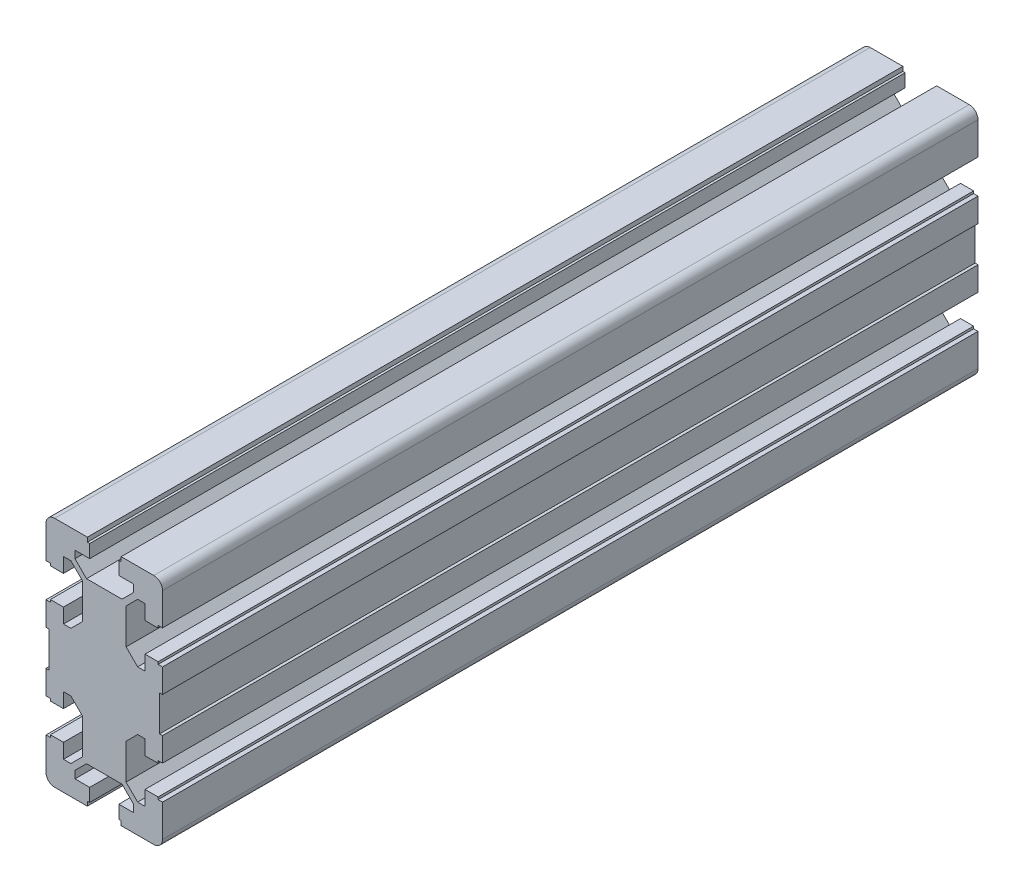
SolidWorks part; units mm, degrees
ref_plane "Front Plane" through (0, 0, 0) normal (0, 0, 1) x (1, 0, 0)
ref_plane "Top Plane" through (0, 0, 0) normal (0, 1, 0) x (1, 0, 0)
ref_plane "Right Plane" through (0, 0, 0) normal (1, 0, 0) x (0, 0, -1)
sketch "Sketch1" plane through (0, 0, 0) normal (0, 0, 1) x (1, 0, 0)
  line L0 (10.6358, -8.0584) -> (17, -8.0584)
  line L1 (19, -6.1084) -> (20, -6.1084)
  line L2 (19, 6.1084) -> (19, -6.1084)
  line L3 (-10.05, -34) -> (-10.05, -31.4642)
  line L4 (-18.5, -34.6084) -> (-18.5, -29.6084)
  line L5 (-20, -25.9084) -> (-20, -37)
  line L6 (17, -8.0584) -> (17, 8.0584)
  line L7 (5.5, -14.6084) -> (2.3979, -14.6084)
  line L8 (-17, -40) -> (-5.8, -40)
  line L9 (-5, -34) -> (-10.05, -34)
  line L10 (-11.75, -34.6084) -> (-11.75, -35.6084)
  line L11 (-11.75, -35.6084) -> (-9.5, -35.6084)
  line L12 (-9.5, -38.6084) -> (-14.5, -38.6084)
  line L13 (-14.5, -38.6084) -> (-14.5, -37.3584)
  line L14 (-17.25, -34.6084) -> (-18.5, -34.6084)
  line L15 (4.5833, -18.1101) -> (5.5, -17.7105)
  line L16 (-5.8, -40) -> (-5.8, -38.5)
  line L17 (-5.8, -38.5) -> (-5, -38.5)
  line L18 (-5, -38.5) -> (-5, -34)
  line L19 (2.3979, -14.6084) -> (1.9983, -15.5251)
  line L20 (5.5, -17.7105) -> (5.5, -14.6084)
  line L21 (18.5, -15.1084) -> (14, -15.1084)
  line L22 (18.5, -14.3084) -> (18.5, -15.1084)
  line L23 (14, -10.0584) -> (11.4642, -10.0584)
  line L24 (14, -15.1084) -> (14, -10.0584)
  line L25 (20, -14.3084) -> (18.5, -14.3084)
  line L26 (0, 44.6651) -> (0, -44.6651) construction
  line L27 (11.4642, -10.0584) -> (7.5, -14.0226)
  line L28 (5.5, -25.6084) -> (5.5, -22.5063)
  line L29 (2.3979, -25.6084) -> (5.5, -25.6084)
  line L30 (1.9983, -24.6917) -> (2.3979, -25.6084)
  line L31 (5.5, -22.5063) -> (4.5833, -22.1067)
  line L32 (14, -25.1084) -> (18.5, -25.1084)
  line L33 (18.5, -25.1084) -> (18.5, -25.9084)
  line L34 (18.5, -25.9084) -> (20, -25.9084)
  line L35 (11.4642, -30.1584) -> (14, -30.1584)
  line L36 (15.5, -31.8584) -> (14.5, -31.8584)
  line L37 (15.5, -29.6084) -> (15.5, -31.8584)
  line L38 (14, -30.1584) -> (14, -25.1084)
  line L39 (-20, -6.1084) -> (-20, -14.3084)
  line L40 (-6.0858, -12.6084) -> (-10.6358, -8.0584)
  line L41 (-7.5, -14.0226) -> (-7.5, -26.1942)
  line L42 (10.05, -31.4642) -> (6.0858, -27.5)
  line L43 (-7.5, -26.1942) -> (-11.4642, -30.1584)
  line L44 (-10.05, -31.4642) -> (-6.0858, -27.5)
  line L45 (-14, -30.1584) -> (-14, -25.1084)
  line L46 (-15.5, -29.6084) -> (-15.5, -31.8584)
  line L47 (-15.5, -31.8584) -> (-14.5, -31.8584)
  line L48 (-11.4642, -30.1584) -> (-14, -30.1584)
  line L49 (-18.5, -25.9084) -> (-20, -25.9084)
  line L50 (-18.5, -25.1084) -> (-18.5, -25.9084)
  line L51 (-14, -25.1084) -> (-18.5, -25.1084)
  line L52 (7.5, -26.1942) -> (11.4642, -30.1584)
  line L53 (-6.0858, -27.5) -> (6.0858, -27.5)
  line L54 (7.5, -14.0226) -> (7.5, -26.1942)
  line L55 (-5.5, -22.5063) -> (-4.5833, -22.1067)
  line L56 (-1.9983, -24.6917) -> (-2.3979, -25.6084)
  line L57 (-2.3979, -25.6084) -> (-5.5, -25.6084)
  line L58 (-5.5, -25.6084) -> (-5.5, -22.5063)
  line L59 (6.0858, -12.6084) -> (10.6358, -8.0584)
  line L60 (20, -6.1084) -> (20, -14.3084)
  line L61 (5, -38.5) -> (5, -34)
  line L62 (5.8, -38.5) -> (5, -38.5)
  line L63 (-11.4642, -10.0584) -> (-7.5, -14.0226)
  line L64 (-20, -14.3084) -> (-18.5, -14.3084)
  line L65 (-14, -15.1084) -> (-14, -10.0584)
  line L66 (-14, -10.0584) -> (-11.4642, -10.0584)
  line L67 (-18.5, -14.3084) -> (-18.5, -15.1084)
  line L68 (-18.5, -15.1084) -> (-14, -15.1084)
  line L69 (5.8, -40) -> (5.8, -38.5)
  line L70 (-5.5, -17.7105) -> (-5.5, -14.6084)
  line L71 (-2.3979, -14.6084) -> (-1.9983, -15.5251)
  line L72 (17.25, -34.6084) -> (18.5, -34.6084)
  line L73 (-4.5833, -18.1101) -> (-5.5, -17.7105)
  line L74 (14.5, -38.6084) -> (14.5, -37.3584)
  line L75 (6.0858, -12.6084) -> (-6.0858, -12.6084)
  line L76 (-5.5, -14.6084) -> (-2.3979, -14.6084)
  line L77 (9.5, -38.6084) -> (14.5, -38.6084)
  line L78 (11.75, -35.6084) -> (9.5, -35.6084)
  line L79 (-17, -8.0584) -> (-17, 8.0584)
  line L80 (-19, 6.1084) -> (-19, -6.1084)
  line L81 (-19, -6.1084) -> (-20, -6.1084)
  line L82 (-10.6358, -8.0584) -> (-17, -8.0584)
  line L83 (11.75, -34.6084) -> (11.75, -35.6084)
  line L84 (5, -34) -> (10.05, -34)
  line L85 (17, -40) -> (5.8, -40)
  line L86 (20, -25.9084) -> (20, -37)
  line L87 (18.5, -34.6084) -> (18.5, -29.6084)
  line L88 (10.05, -34) -> (10.05, -31.4642)
  line L89 (10.05, 34) -> (10.05, 31.4642)
  line L90 (18.5, 34.6084) -> (18.5, 29.6084)
  line L91 (20, 25.9084) -> (20, 37)
  line L92 (17, 40) -> (5.8, 40)
  line L93 (5, 34) -> (10.05, 34)
  line L94 (11.75, 34.6084) -> (11.75, 35.6084)
  line L95 (-10.6358, 8.0584) -> (-17, 8.0584)
  line L96 (-19, 6.1084) -> (-20, 6.1084)
  line L97 (11.75, 35.6084) -> (9.5, 35.6084)
  line L98 (9.5, 38.6084) -> (14.5, 38.6084)
  line L99 (-5.5, 14.6084) -> (-2.3979, 14.6084)
  line L100 (6.0858, 12.6084) -> (-6.0858, 12.6084)
  line L101 (14.5, 38.6084) -> (14.5, 37.3584)
  line L102 (-4.5833, 18.1101) -> (-5.5, 17.7105)
  line L103 (17.25, 34.6084) -> (18.5, 34.6084)
  line L104 (-2.3979, 14.6084) -> (-1.9983, 15.5251)
  line L105 (-5.5, 17.7105) -> (-5.5, 14.6084)
  line L106 (5.8, 40) -> (5.8, 38.5)
  line L107 (-18.5, 15.1084) -> (-14, 15.1084)
  line L108 (-18.5, 14.3084) -> (-18.5, 15.1084)
  line L109 (-14, 10.0584) -> (-11.4642, 10.0584)
  line L110 (-14, 15.1084) -> (-14, 10.0584)
  line L111 (-20, 14.3084) -> (-18.5, 14.3084)
  line L112 (-11.4642, 10.0584) -> (-7.5, 14.0226)
  line L113 (5.8, 38.5) -> (5, 38.5)
  line L114 (5, 38.5) -> (5, 34)
  line L115 (20, 6.1084) -> (20, 14.3084)
  line L116 (6.0858, 12.6084) -> (10.6358, 8.0584)
  line L117 (-5.5, 25.6084) -> (-5.5, 22.5063)
  line L118 (-2.3979, 25.6084) -> (-5.5, 25.6084)
  line L119 (-1.9983, 24.6917) -> (-2.3979, 25.6084)
  line L120 (-5.5, 22.5063) -> (-4.5833, 22.1067)
  line L121 (7.5, 14.0226) -> (7.5, 26.1942)
  line L122 (-6.0858, 27.5) -> (6.0858, 27.5)
  line L123 (7.5, 26.1942) -> (11.4642, 30.1584)
  line L124 (-14, 25.1084) -> (-18.5, 25.1084)
  line L125 (-18.5, 25.1084) -> (-18.5, 25.9084)
  line L126 (-18.5, 25.9084) -> (-20, 25.9084)
  line L127 (-11.4642, 30.1584) -> (-14, 30.1584)
  line L128 (-15.5, 31.8584) -> (-14.5, 31.8584)
  line L129 (-15.5, 29.6084) -> (-15.5, 31.8584)
  line L130 (-14, 30.1584) -> (-14, 25.1084)
  line L131 (-10.05, 31.4642) -> (-6.0858, 27.5)
  line L132 (-7.5, 26.1942) -> (-11.4642, 30.1584)
  line L133 (10.05, 31.4642) -> (6.0858, 27.5)
  line L134 (-7.5, 14.0226) -> (-7.5, 26.1942)
  line L135 (-6.0858, 12.6084) -> (-10.6358, 8.0584)
  line L136 (-20, 6.1084) -> (-20, 14.3084)
  line L137 (14, 30.1584) -> (14, 25.1084)
  line L138 (15.5, 29.6084) -> (15.5, 31.8584)
  line L139 (15.5, 31.8584) -> (14.5, 31.8584)
  line L140 (11.4642, 30.1584) -> (14, 30.1584)
  line L141 (18.5, 25.9084) -> (20, 25.9084)
  line L142 (18.5, 25.1084) -> (18.5, 25.9084)
  line L143 (14, 25.1084) -> (18.5, 25.1084)
  line L144 (5.5, 22.5063) -> (4.5833, 22.1067)
  line L145 (1.9983, 24.6917) -> (2.3979, 25.6084)
  line L146 (2.3979, 25.6084) -> (5.5, 25.6084)
  line L147 (5.5, 25.6084) -> (5.5, 22.5063)
  line L148 (11.4642, 10.0584) -> (7.5, 14.0226)
  line L149 (20, 14.3084) -> (18.5, 14.3084)
  line L150 (14, 15.1084) -> (14, 10.0584)
  line L151 (14, 10.0584) -> (11.4642, 10.0584)
  line L152 (18.5, 14.3084) -> (18.5, 15.1084)
  line L153 (18.5, 15.1084) -> (14, 15.1084)
  line L154 (5.5, 17.7105) -> (5.5, 14.6084)
  line L155 (2.3979, 14.6084) -> (1.9983, 15.5251)
  line L156 (-5, 38.5) -> (-5, 34)
  line L157 (-5.8, 38.5) -> (-5, 38.5)
  line L158 (-5.8, 40) -> (-5.8, 38.5)
  line L159 (4.5833, 18.1101) -> (5.5, 17.7105)
  line L160 (-17.25, 34.6084) -> (-18.5, 34.6084)
  line L161 (-14.5, 38.6084) -> (-14.5, 37.3584)
  line L162 (-9.5, 38.6084) -> (-14.5, 38.6084)
  line L163 (-11.75, 35.6084) -> (-9.5, 35.6084)
  line L164 (-11.75, 34.6084) -> (-11.75, 35.6084)
  line L165 (-5, 34) -> (-10.05, 34)
  line L166 (-17, 40) -> (-5.8, 40)
  line L167 (5.5, 14.6084) -> (2.3979, 14.6084)
  line L168 (-20, 25.9084) -> (-20, 37)
  line L169 (-18.5, 34.6084) -> (-18.5, 29.6084)
  line L170 (-10.05, 34) -> (-10.05, 31.4642)
  line L171 (19, 6.1084) -> (20, 6.1084)
  line L172 (10.6358, 8.0584) -> (17, 8.0584)
  line L175 (-39.3803, 0) -> (39.3803, 0) construction
  arc A0 (-11.75, -34.6084) -> (-14.5, -31.8584) centre (-14.5, -34.6084) ccw
  arc A1 (15.5, -29.6084) -> (18.5, -29.6084) centre (17, -29.6084) cw
  arc A2 (-9.5, -38.6084) -> (-9.5, -35.6084) centre (-9.5, -37.1084) ccw
  arc A3 (-20, -37) -> (-17, -40) centre (-17, -37) ccw
  arc A4 (-17.25, -34.6084) -> (-14.5, -37.3584) centre (-14.5, -34.6084) ccw
  arc A5 (4.5833, -18.1101) -> (4.5833, -22.1067) centre (0, -20.1084) cw
  arc A6 (17.25, -34.6084) -> (14.5, -37.3584) centre (14.5, -34.6084) cw
  arc A7 (20, -37) -> (17, -40) centre (17, -37) cw
  arc A8 (9.5, -38.6084) -> (9.5, -35.6084) centre (9.5, -37.1084) cw
  arc A9 (11.75, -34.6084) -> (14.5, -31.8584) centre (14.5, -34.6084) cw
  arc A10 (-4.5833, -18.1101) -> (-4.5833, -22.1067) centre (0, -20.1084) ccw
  arc A11 (-15.5, -29.6084) -> (-18.5, -29.6084) centre (-17, -29.6084) ccw
  arc A12 (-1.9983, -24.6917) -> (1.9983, -24.6917) centre (0, -20.1084) ccw
  arc A13 (1.9983, -15.5251) -> (-1.9983, -15.5251) centre (0, -20.1084) ccw
  arc A14 (1.9983, 15.5251) -> (-1.9983, 15.5251) centre (0, 20.1084) cw
  arc A15 (-1.9983, 24.6917) -> (1.9983, 24.6917) centre (0, 20.1084) cw
  arc A16 (-15.5, 29.6084) -> (-18.5, 29.6084) centre (-17, 29.6084) cw
  arc A17 (-4.5833, 18.1101) -> (-4.5833, 22.1067) centre (0, 20.1084) cw
  arc A18 (11.75, 34.6084) -> (14.5, 31.8584) centre (14.5, 34.6084) ccw
  arc A19 (9.5, 38.6084) -> (9.5, 35.6084) centre (9.5, 37.1084) ccw
  arc A20 (20, 37) -> (17, 40) centre (17, 37) ccw
  arc A21 (17.25, 34.6084) -> (14.5, 37.3584) centre (14.5, 34.6084) ccw
  arc A22 (4.5833, 18.1101) -> (4.5833, 22.1067) centre (0, 20.1084) ccw
  arc A23 (-17.25, 34.6084) -> (-14.5, 37.3584) centre (-14.5, 34.6084) cw
  arc A24 (-20, 37) -> (-17, 40) centre (-17, 37) cw
  arc A25 (-9.5, 38.6084) -> (-9.5, 35.6084) centre (-9.5, 37.1084) cw
  arc A26 (15.5, 29.6084) -> (18.5, 29.6084) centre (17, 29.6084) ccw
  arc A27 (-11.75, 34.6084) -> (-14.5, 31.8584) centre (-14.5, 34.6084) cw
  point P44 (0, -12.6084)
  point P77 (0, -27.5)
  point P143 (0, 27.5)
  point P144 (0, 12.6084)
  point P156 (-19, 0)
  point P157 (-17, 0)
  point P230 (17, 0)
  point P231 (19, 0)
  dimension "D3" = 10
  dimension "D1" = 40
  dimension "D2" = 80
  dimension "D4" = 10
  dimension "D5" = 10
extrude "Extrude1" add sketch "Sketch1" against normal blind 200
sketch "Sketch2" plane through (0, 0, 0) normal (0, 0, 1) x (1, 0, 0)
  line L96 (-17, -40) -> (-5.8, -40)
  line L97 (-5.8, -40) -> (-5.8, -38.5)
  line L98 (-5.8, -38.5) -> (-5, -38.5)
  line L99 (-5, -38.5) -> (-5, -34)
  line L100 (-5, -34) -> (-10.05, -34)
  line L101 (-10.05, -34) -> (-10.05, -31.4642)
  line L102 (-10.05, -31.4642) -> (-6.0858, -27.5)
  line L103 (-6.0858, -27.5) -> (6.0858, -27.5)
  line L104 (6.0858, -27.5) -> (10.05, -31.4642)
  line L105 (10.05, -31.4642) -> (10.05, -34)
  line L106 (10.05, -34) -> (5, -34)
  line L107 (5, -34) -> (5, -38.5)
  line L108 (5, -38.5) -> (5.8, -38.5)
  line L109 (5.8, -38.5) -> (5.8, -40)
  line L110 (5.8, -40) -> (17, -40)
  line L111 (20, -37) -> (20, -25.9084)
  line L112 (20, -25.9084) -> (18.5, -25.9084)
  line L113 (18.5, -25.9084) -> (18.5, -25.1084)
  line L114 (18.5, -25.1084) -> (14, -25.1084)
  line L115 (14, -25.1084) -> (14, -30.1584)
  line L116 (14, -30.1584) -> (11.4642, -30.1584)
  line L117 (11.4642, -30.1584) -> (7.5, -26.1942)
  line L118 (7.5, -26.1942) -> (7.5, -14.0226)
  line L119 (7.5, -14.0226) -> (11.4642, -10.0584)
  line L120 (11.4642, -10.0584) -> (14, -10.0584)
  line L121 (14, -10.0584) -> (14, -15.1084)
  line L122 (14, -15.1084) -> (18.5, -15.1084)
  line L123 (18.5, -15.1084) -> (18.5, -14.3084)
  line L124 (18.5, -14.3084) -> (20, -14.3084)
  line L125 (20, -14.3084) -> (20, -6.1084)
  line L126 (20, -6.1084) -> (19, -6.1084)
  line L127 (19, -6.1084) -> (19, 6.1084)
  line L128 (19, 6.1084) -> (20, 6.1084)
  line L129 (20, 6.1084) -> (20, 14.3084)
  line L130 (20, 14.3084) -> (18.5, 14.3084)
  line L131 (18.5, 14.3084) -> (18.5, 15.1084)
  line L132 (18.5, 15.1084) -> (14, 15.1084)
  line L133 (14, 15.1084) -> (14, 10.0584)
  line L134 (14, 10.0584) -> (11.4642, 10.0584)
  line L135 (11.4642, 10.0584) -> (7.5, 14.0226)
  line L136 (7.5, 14.0226) -> (7.5, 26.1942)
  line L137 (7.5, 26.1942) -> (11.4642, 30.1584)
  line L138 (11.4642, 30.1584) -> (14, 30.1584)
  line L139 (14, 30.1584) -> (14, 25.1084)
  line L140 (14, 25.1084) -> (18.5, 25.1084)
  line L141 (18.5, 25.1084) -> (18.5, 25.9084)
  line L142 (18.5, 25.9084) -> (20, 25.9084)
  line L143 (20, 25.9084) -> (20, 37)
  line L144 (17, 40) -> (5.8, 40)
  line L145 (5.8, 40) -> (5.8, 38.5)
  line L146 (5.8, 38.5) -> (5, 38.5)
  line L147 (5, 38.5) -> (5, 34)
  line L148 (5, 34) -> (10.05, 34)
  line L149 (10.05, 34) -> (10.05, 31.4642)
  line L150 (10.05, 31.4642) -> (6.0858, 27.5)
  line L151 (6.0858, 27.5) -> (-6.0858, 27.5)
  line L152 (-6.0858, 27.5) -> (-10.05, 31.4642)
  line L153 (-10.05, 31.4642) -> (-10.05, 34)
  line L154 (-10.05, 34) -> (-5, 34)
  line L155 (-5, 34) -> (-5, 38.5)
  line L156 (-5, 38.5) -> (-5.8, 38.5)
  line L157 (-5.8, 38.5) -> (-5.8, 40)
  line L158 (-5.8, 40) -> (-17, 40)
  line L159 (-20, 37) -> (-20, 25.9084)
  line L160 (-20, 25.9084) -> (-18.5, 25.9084)
  line L161 (-18.5, 25.9084) -> (-18.5, 25.1084)
  line L162 (-18.5, 25.1084) -> (-14, 25.1084)
  line L163 (-14, 25.1084) -> (-14, 30.1584)
  line L164 (-14, 30.1584) -> (-11.4642, 30.1584)
  line L165 (-11.4642, 30.1584) -> (-7.5, 26.1942)
  line L166 (-7.5, 26.1942) -> (-7.5, 14.0226)
  line L167 (-7.5, 14.0226) -> (-11.4642, 10.0584)
  line L168 (-11.4642, 10.0584) -> (-14, 10.0584)
  line L169 (-14, 10.0584) -> (-14, 15.1084)
  line L170 (-14, 15.1084) -> (-18.5, 15.1084)
  line L171 (-18.5, 15.1084) -> (-18.5, 14.3084)
  line L172 (-18.5, 14.3084) -> (-20, 14.3084)
  line L173 (-20, 14.3084) -> (-20, 6.1084)
  line L174 (-20, 6.1084) -> (-19, 6.1084)
  line L175 (-19, 6.1084) -> (-19, -6.1084)
  line L176 (-19, -6.1084) -> (-20, -6.1084)
  line L177 (-20, -6.1084) -> (-20, -14.3084)
  line L178 (-20, -14.3084) -> (-18.5, -14.3084)
  line L179 (-18.5, -14.3084) -> (-18.5, -15.1084)
  line L180 (-18.5, -15.1084) -> (-14, -15.1084)
  line L181 (-14, -15.1084) -> (-14, -10.0584)
  line L182 (-14, -10.0584) -> (-11.4642, -10.0584)
  line L183 (-11.4642, -10.0584) -> (-7.5, -14.0226)
  line L184 (-7.5, -14.0226) -> (-7.5, -26.1942)
  line L185 (-7.5, -26.1942) -> (-11.4642, -30.1584)
  line L186 (-11.4642, -30.1584) -> (-14, -30.1584)
  line L187 (-14, -30.1584) -> (-14, -25.1084)
  line L188 (-14, -25.1084) -> (-18.5, -25.1084)
  line L189 (-18.5, -25.1084) -> (-18.5, -25.9084)
  line L190 (-18.5, -25.9084) -> (-20, -25.9084)
  line L191 (-20, -25.9084) -> (-20, -37)
  line L192 (-17, -40) -> (-5.8, -40)
  line L193 (-5.8, -40) -> (-5.8, -38.5)
  line L194 (-5.8, -38.5) -> (-5, -38.5)
  line L195 (-5, -38.5) -> (-5, -34)
  line L196 (-5, -34) -> (-10.05, -34)
  line L197 (-10.05, -34) -> (-10.05, -31.4642)
  line L198 (-10.05, -31.4642) -> (-6.0858, -27.5)
  line L199 (-6.0858, -27.5) -> (6.0858, -27.5)
  line L200 (6.0858, -27.5) -> (10.05, -31.4642)
  line L201 (10.05, -31.4642) -> (10.05, -34)
  line L202 (10.05, -34) -> (5, -34)
  line L203 (5, -34) -> (5, -38.5)
  line L204 (5, -38.5) -> (5.8, -38.5)
  line L205 (5.8, -38.5) -> (5.8, -40)
  line L206 (5.8, -40) -> (17, -40)
  line L207 (20, -37) -> (20, -25.9084)
  line L208 (20, -25.9084) -> (18.5, -25.9084)
  line L209 (18.5, -25.9084) -> (18.5, -25.1084)
  line L210 (18.5, -25.1084) -> (14, -25.1084)
  line L211 (14, -25.1084) -> (14, -30.1584)
  line L212 (14, -30.1584) -> (11.4642, -30.1584)
  line L213 (11.4642, -30.1584) -> (7.5, -26.1942)
  line L214 (7.5, -26.1942) -> (7.5, -14.0226)
  line L215 (7.5, -14.0226) -> (11.4642, -10.0584)
  line L216 (11.4642, -10.0584) -> (14, -10.0584)
  line L217 (14, -10.0584) -> (14, -15.1084)
  line L218 (14, -15.1084) -> (18.5, -15.1084)
  line L219 (18.5, -15.1084) -> (18.5, -14.3084)
  line L220 (18.5, -14.3084) -> (20, -14.3084)
  line L221 (20, -14.3084) -> (20, -6.1084)
  line L222 (20, -6.1084) -> (19, -6.1084)
  line L223 (19, -6.1084) -> (19, 6.1084)
  line L224 (19, 6.1084) -> (20, 6.1084)
  line L225 (20, 6.1084) -> (20, 14.3084)
  line L226 (20, 14.3084) -> (18.5, 14.3084)
  line L227 (18.5, 14.3084) -> (18.5, 15.1084)
  line L228 (18.5, 15.1084) -> (14, 15.1084)
  line L229 (14, 15.1084) -> (14, 10.0584)
  line L230 (14, 10.0584) -> (11.4642, 10.0584)
  line L231 (11.4642, 10.0584) -> (7.5, 14.0226)
  line L232 (7.5, 14.0226) -> (7.5, 26.1942)
  line L233 (7.5, 26.1942) -> (11.4642, 30.1584)
  line L234 (11.4642, 30.1584) -> (14, 30.1584)
  line L235 (14, 30.1584) -> (14, 25.1084)
  line L236 (14, 25.1084) -> (18.5, 25.1084)
  line L237 (18.5, 25.1084) -> (18.5, 25.9084)
  line L238 (18.5, 25.9084) -> (20, 25.9084)
  line L239 (20, 25.9084) -> (20, 37)
  line L240 (17, 40) -> (5.8, 40)
  line L241 (5.8, 40) -> (5.8, 38.5)
  line L242 (5.8, 38.5) -> (5, 38.5)
  line L243 (5, 38.5) -> (5, 34)
  line L244 (5, 34) -> (10.05, 34)
  line L245 (10.05, 34) -> (10.05, 31.4642)
  line L246 (10.05, 31.4642) -> (6.0858, 27.5)
  line L247 (6.0858, 27.5) -> (-6.0858, 27.5)
  line L248 (-6.0858, 27.5) -> (-10.05, 31.4642)
  line L249 (-10.05, 31.4642) -> (-10.05, 34)
  line L250 (-10.05, 34) -> (-5, 34)
  line L251 (-5, 34) -> (-5, 38.5)
  line L252 (-5, 38.5) -> (-5.8, 38.5)
  line L253 (-5.8, 38.5) -> (-5.8, 40)
  line L254 (-5.8, 40) -> (-17, 40)
  line L255 (-20, 37) -> (-20, 25.9084)
  line L256 (-20, 25.9084) -> (-18.5, 25.9084)
  line L257 (-18.5, 25.9084) -> (-18.5, 25.1084)
  line L258 (-18.5, 25.1084) -> (-14, 25.1084)
  line L259 (-14, 25.1084) -> (-14, 30.1584)
  line L260 (-14, 30.1584) -> (-11.4642, 30.1584)
  line L261 (-11.4642, 30.1584) -> (-7.5, 26.1942)
  line L262 (-7.5, 26.1942) -> (-7.5, 14.0226)
  line L263 (-7.5, 14.0226) -> (-11.4642, 10.0584)
  line L264 (-11.4642, 10.0584) -> (-14, 10.0584)
  line L265 (-14, 10.0584) -> (-14, 15.1084)
  line L266 (-14, 15.1084) -> (-18.5, 15.1084)
  line L267 (-18.5, 15.1084) -> (-18.5, 14.3084)
  line L268 (-18.5, 14.3084) -> (-20, 14.3084)
  line L269 (-20, 14.3084) -> (-20, 6.1084)
  line L270 (-20, 6.1084) -> (-19, 6.1084)
  line L271 (-19, 6.1084) -> (-19, -6.1084)
  line L272 (-19, -6.1084) -> (-20, -6.1084)
  line L273 (-20, -6.1084) -> (-20, -14.3084)
  line L274 (-20, -14.3084) -> (-18.5, -14.3084)
  line L275 (-18.5, -14.3084) -> (-18.5, -15.1084)
  line L276 (-18.5, -15.1084) -> (-14, -15.1084)
  line L277 (-14, -15.1084) -> (-14, -10.0584)
  line L278 (-14, -10.0584) -> (-11.4642, -10.0584)
  line L279 (-11.4642, -10.0584) -> (-7.5, -14.0226)
  line L280 (-7.5, -14.0226) -> (-7.5, -26.1942)
  line L281 (-7.5, -26.1942) -> (-11.4642, -30.1584)
  line L282 (-11.4642, -30.1584) -> (-14, -30.1584)
  line L283 (-14, -30.1584) -> (-14, -25.1084)
  line L284 (-14, -25.1084) -> (-18.5, -25.1084)
  line L285 (-18.5, -25.1084) -> (-18.5, -25.9084)
  line L286 (-18.5, -25.9084) -> (-20, -25.9084)
  line L287 (-20, -25.9084) -> (-20, -37)
  arc A4 (-20, -37) -> (-17, -40) centre (-17, -37) ccw
  arc A5 (17, -40) -> (20, -37) centre (17, -37) ccw
  arc A6 (20, 37) -> (17, 40) centre (17, 37) ccw
  arc A7 (-17, 40) -> (-20, 37) centre (-17, 37) ccw
  arc A8 (-20, -37) -> (-17, -40) centre (-17, -37) ccw
  arc A9 (17, -40) -> (20, -37) centre (17, -37) ccw
  arc A10 (20, 37) -> (17, 40) centre (17, 37) ccw
  arc A11 (-17, 40) -> (-20, 37) centre (-17, 37) ccw
  dimension "D1" = 0
extrude "Boss-Extrude1" add sketch "Sketch2" along normal blind 80
